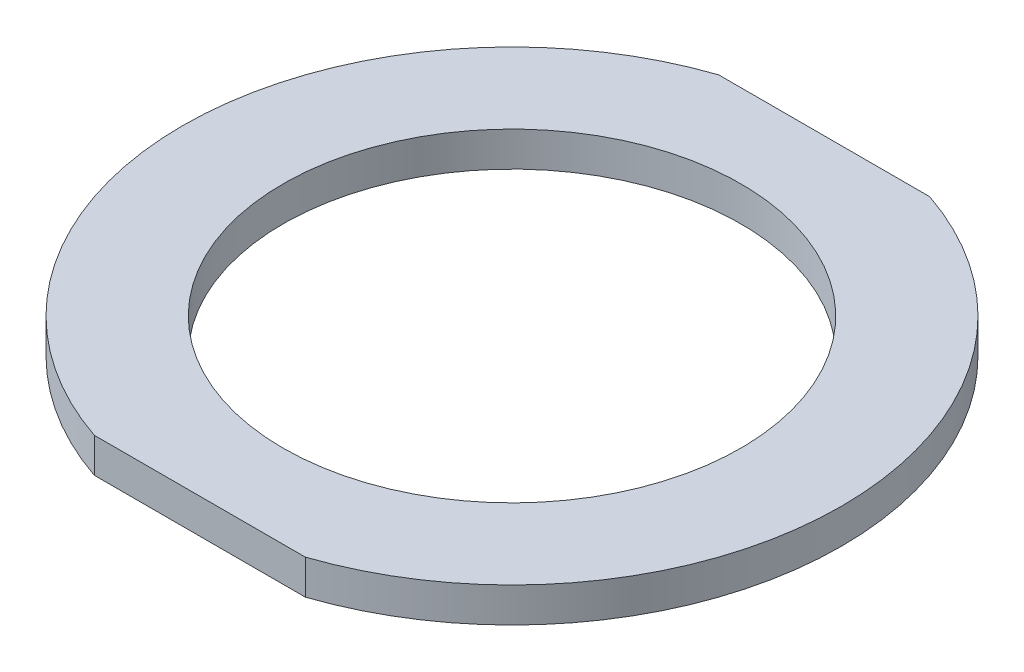
SolidWorks part; units mm, degrees
material "Сосна"
ref_plane "Спереди" through (0, 0, 0) normal (0, 0, 1) x (1, 0, 0)
ref_plane "Сверху" through (0, 0, 0) normal (0, 1, 0) x (1, 0, 0)
ref_plane "Справа" through (0, 0, 0) normal (1, 0, 0) x (0, 0, -1)
sketch "Эскиз1" plane through (0, 0, 0) normal (0, 1, 0) x (1, 0, 0)
  circle A0 centre (0, 0) radius 47.5
  circle A1 centre (0, 0) radius 33
  dimension "D1" = 66
  dimension "D2" = 95
extrude "Бобышка-Вытянуть1" add sketch "Эскиз1" along normal blind 5
sketch "Эскиз2" plane through (0, 0, 0) normal (1, 0, 0) x (0, 0, -1)
  line L1 (45, -15) -> (-45, -15) construction
  line L2 (45, -15) -> (45, 15)
  line L3 (45, 15) -> (-45, 15) construction
  line L4 (-45, -15) -> (-45, 15)
  line L5 (45, -15) -> (-45, 15) construction
  line L6 (45, 15) -> (-45, -15) construction
  line L7 (-45, 15) -> (-55, 15)
  line L8 (-45, 15) -> (-45, -15)
  line L9 (-45, -15) -> (-55, -15)
  line L10 (-55, 15) -> (-55, -15)
  line L11 (45, 15) -> (55, 15)
  line L12 (45, 15) -> (45, -15)
  line L13 (45, -15) -> (55, -15)
  line L14 (55, 15) -> (55, -15)
  point P0 (0, 0)
  dimension "D1" = 30
  dimension "D2" = 90
  dimension "D3" = 10
  dimension "D4" = 10
extrude "Вырез-Вытянуть1" cut sketch "Эскиз2" against normal mid plane 50 contours L7 L10 L9 L4 | L14 L11 L2 L13
